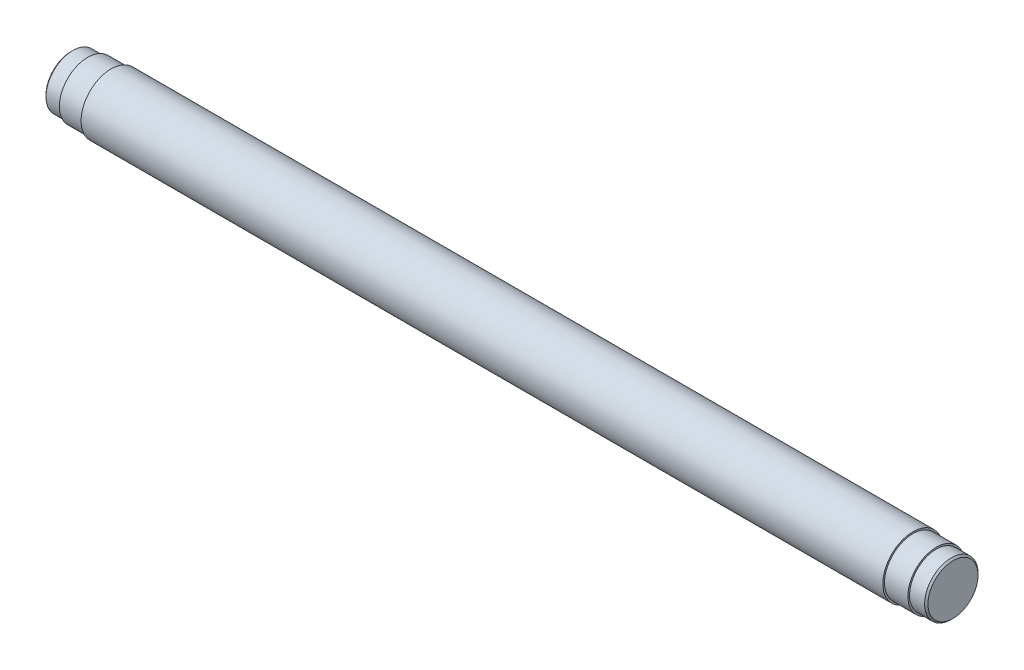
SolidWorks part; units mm, degrees
ref_plane "前视基准面" through (0, 0, 0) normal (0, 0, 1) x (1, 0, 0)
ref_plane "上视基准面" through (0, 0, 0) normal (0, 1, 0) x (1, 0, 0)
ref_plane "右视基准面" through (0, 0, 0) normal (1, 0, 0) x (0, 0, -1)
sketch "草图1" plane through (0, 0, 0) normal (0, 1, 0) x (1, 0, 0)
  line L0 (-102.4872, 0) -> (112.9676, 0) construction
  line L1 (0, 0) -> (0, 8)
  line L2 (0, 8) -> (5, 8)
  line L3 (5, 8) -> (5, 8.5)
  line L4 (5, 8.5) -> (12, 8.5)
  line L5 (12, 8.5) -> (12, 9)
  line L6 (12, 9) -> (252, 9)
  line L7 (252, 9) -> (252, 8.5)
  line L8 (252, 8.5) -> (259, 8.5)
  line L9 (259, 8.5) -> (259, 8)
  line L10 (259, 8) -> (264, 8)
  line L11 (264, 8) -> (264, 0)
  line L12 (0, 0) -> (264, 0)
revolve "旋转1" add sketch "草图1" angle 360 about L0
chamfer "倒角1" distance 0.5 angle 45 1 edges at (264, 0, 8)
chamfer "倒角2" distance 0.5 angle 45 1 edges at (0, 0, 8)
